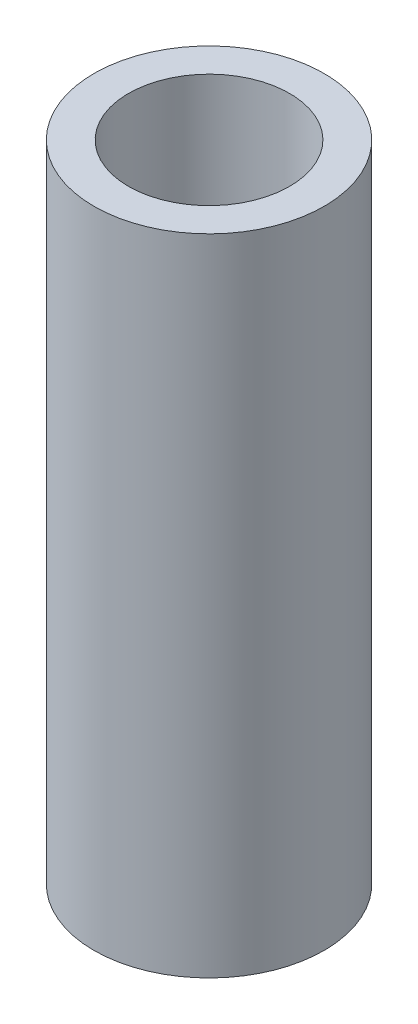
SolidWorks part; units mm, degrees
ref_plane "Front Plane" through (0, 0, 0) normal (0, 0, 1) x (1, 0, 0)
ref_plane "Top Plane" through (0, 0, 0) normal (0, 1, 0) x (1, 0, 0)
ref_plane "Right Plane" through (0, 0, 0) normal (1, 0, 0) x (0, 0, -1)
sketch "Sketch1" plane through (0, 0, 0) normal (0, 1, 0) x (1, 0, 0)
  circle A0 centre (0, 0) radius 1.75
  circle A1 centre (0, 0) radius 2.5
  dimension "D1" = 3.5
  dimension "D2" = 5
extrude "Boss-Extrude1" add sketch "Sketch1" along normal blind 14
